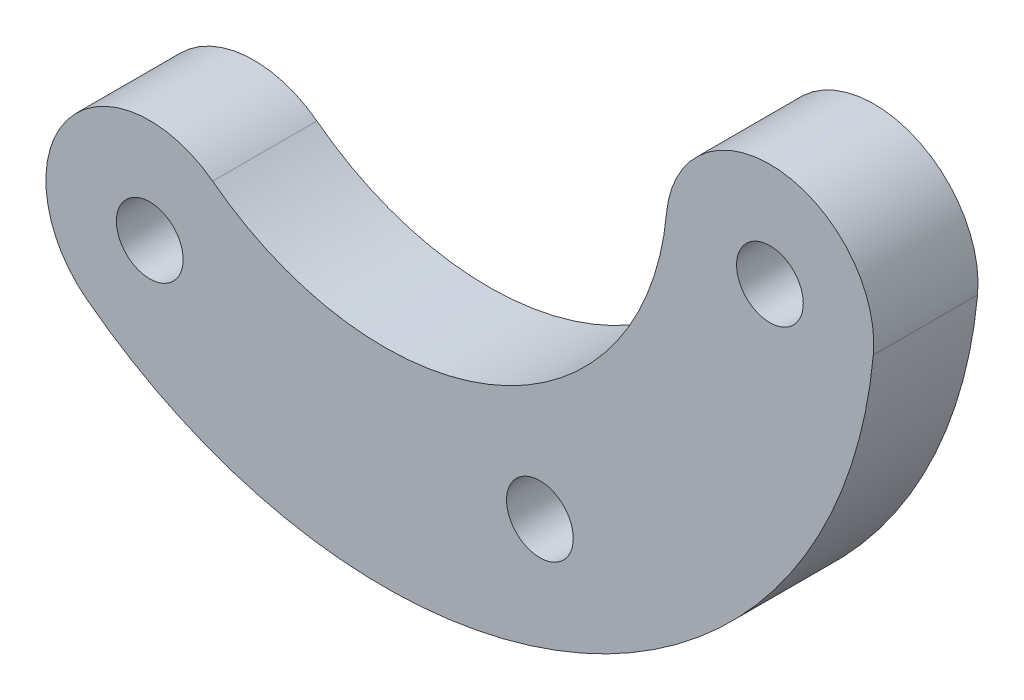
SolidWorks part; units mm, degrees
ref_plane "前视基准面" through (0, 0, 0) normal (0, 0, 1) x (1, 0, 0)
ref_plane "上视基准面" through (0, 0, 0) normal (0, 1, 0) x (1, 0, 0)
ref_plane "右视基准面" through (0, 0, 0) normal (1, 0, 0) x (0, 0, -1)
other "Configuration Table"
sketch "草图1" plane through (0, 0, 0) normal (0, 0, 1) x (1, 0, 0)
  arc A0 (0, 0) -> (29.7406, 13.049) centre (11.2474, 14.7815) ccw construction
  arc A1 (-3.016, -3.9637) -> (34.6995, 12.5845) centre (11.2474, 14.7815) ccw
  arc A2 (3.016, 3.9637) -> (24.7816, 13.5136) centre (11.2474, 14.7815) ccw
  arc A3 (3.016, 3.9637) -> (-3.016, -3.9637) centre (0, 0) ccw
  arc A4 (34.6995, 12.5845) -> (24.7816, 13.5136) centre (29.7406, 13.049) ccw
  circle A5 centre (0, 0) radius 1.6
  circle A7 centre (29.7406, 13.049) radius 1.6
  circle A8 centre (18.7103, -2.2274) radius 1.6
  point P3 (18.7103, -2.2274)
  point P11 (18.7103, -2.2274)
  point P12 (0, 0)
  point P13 (0, 0)
  point P16 (0, 0)
  point P17 (29.7406, 13.049)
  point P20 (18.7103, -2.2274)
extrude "凸台-拉伸1" add sketch "草图1" along normal blind 5
